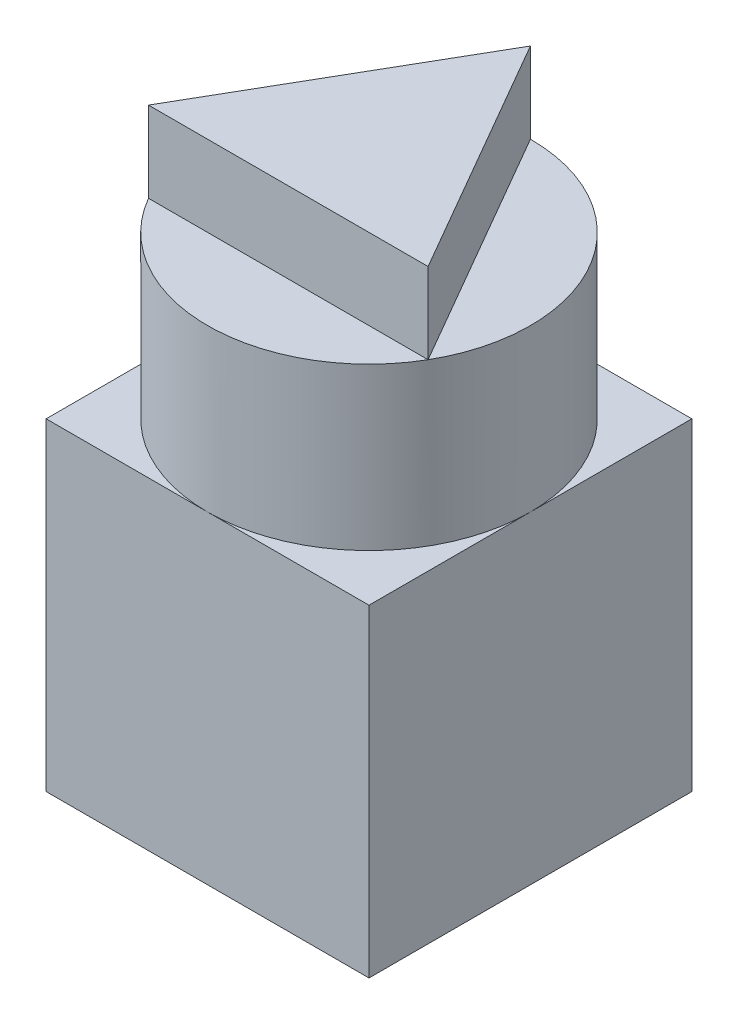
SolidWorks part; units mm, degrees
ref_plane "Front Plane" through (0, 0, 0) normal (0, 0, 1) x (1, 0, 0)
ref_plane "Top Plane" through (0, 0, 0) normal (0, 1, 0) x (1, 0, 0)
ref_plane "Right Plane" through (0, 0, 0) normal (1, 0, 0) x (0, 0, -1)
sketch "Sketch1" plane through (0, 0, 0) normal (0, 1, 0) x (1, 0, 0)
  line L1 (-100, -100) -> (100, -100)
  line L2 (-100, -100) -> (-100, 100)
  line L3 (-100, 100) -> (100, 100)
  line L4 (100, -100) -> (100, 100)
  line L5 (-100, -100) -> (100, 100) construction
  line L6 (-100, 100) -> (100, -100) construction
  point P0 (0, 0)
  dimension "D1" = 200
extrude "Boss-Extrude2" add sketch "Sketch1" along normal blind 200
sketch "Sketch3" plane through (0, 200, 0) normal (0, 1, 0) x (1, 0, 0)
  circle A0 centre (0, 0) radius 100
extrude "Boss-Extrude3" add sketch "Sketch3" along normal blind 100
sketch "Sketch4" plane through (0, 300, 0) normal (0, 1, 0) x (1, 0, 0)
  line L0 (0, 100) -> (-86.6025, -50)
  line L1 (-86.6025, -50) -> (86.6025, -50)
  line L2 (86.6025, -50) -> (0, 100)
  arc A0 (-100, 0) -> (0, -100) centre (0, 0) ccw construction
  arc A1 (0, -100) -> (100, 0) centre (0, 0) ccw construction
extrude "Boss-Extrude4" add sketch "Sketch4" along normal blind 50
